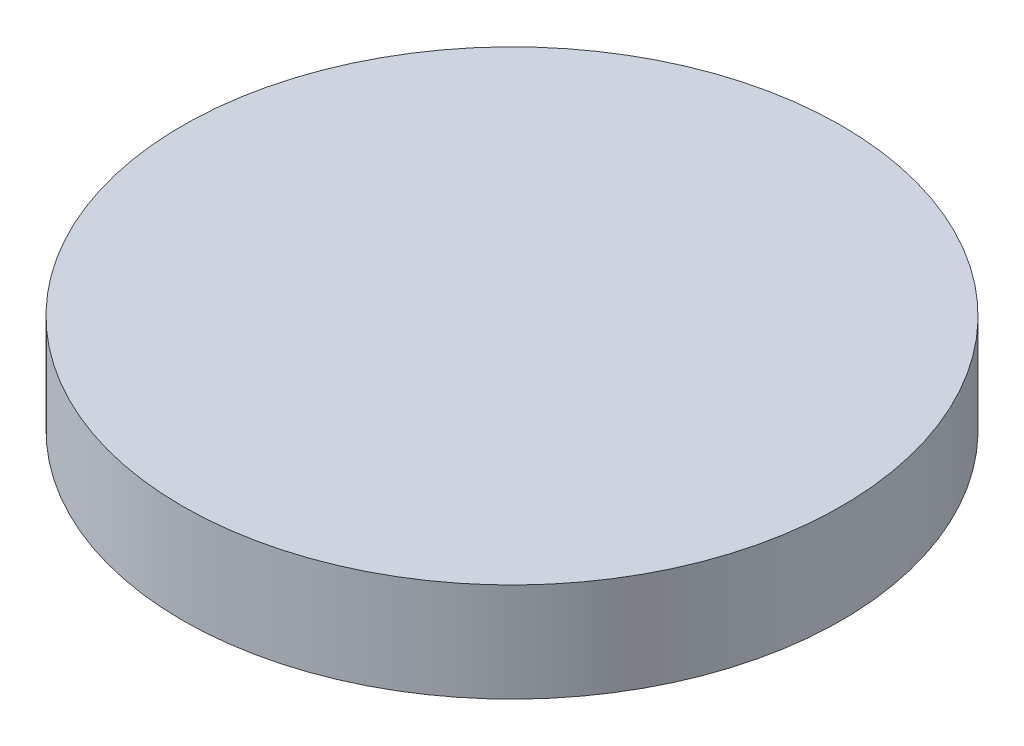
SolidWorks part; units mm, degrees
material "玻璃"
ref_plane "前视基准面" through (0, 0, 0) normal (0, 0, 1) x (1, 0, 0)
ref_plane "上视基准面" through (0, 0, 0) normal (0, 1, 0) x (1, 0, 0)
ref_plane "右视基准面" through (0, 0, 0) normal (1, 0, 0) x (0, 0, -1)
sketch "草图1" plane through (0, 0, 0) normal (0, 1, 0) x (1, 0, 0)
  circle A0 centre (0, 0) radius 5
  dimension "D1" = 10
extrude "1.5mm 镜片" add sketch "草图1" along normal blind 1.5
